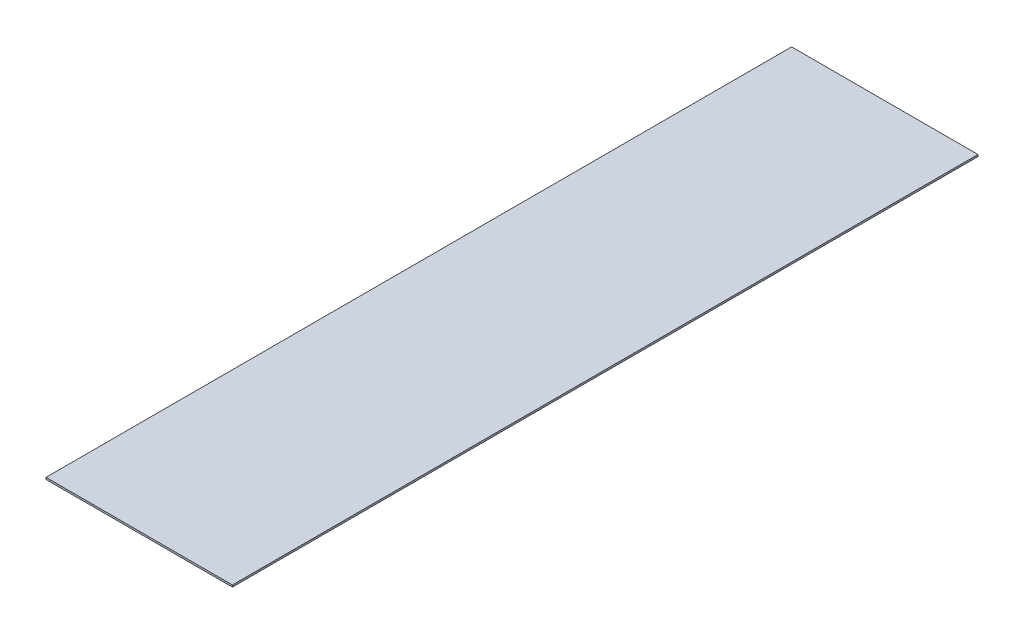
SolidWorks part; units mm, degrees
ref_plane "前视基准面" through (0, 0, 0) normal (0, 0, 1) x (1, 0, 0)
ref_plane "上视基准面" through (0, 0, 0) normal (0, 1, 0) x (1, 0, 0)
ref_plane "右视基准面" through (0, 0, 0) normal (1, 0, 0) x (0, 0, -1)
other "Configuration Table"
sketch "草图1" plane through (0, 0, 0) normal (0, 1, 0) x (1, 0, 0)
  line L1 (0, 0) -> (-400, 0)
  line L2 (0, 0) -> (0, 1600)
  line L3 (0, 1600) -> (-400, 1600)
  line L4 (-400, 0) -> (-400, 1600)
  dimension "D1" = 400
  dimension "D2" = 1600
extrude "凸台-拉伸1" add sketch "草图1" along normal blind 4
